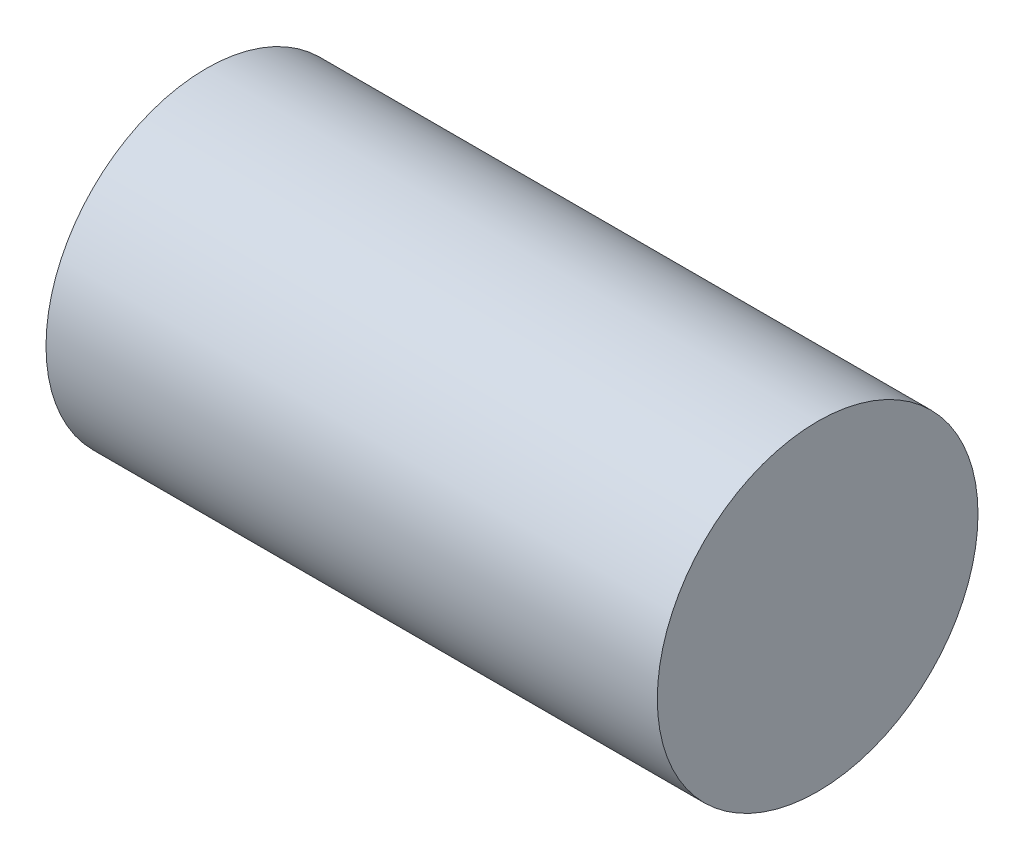
SolidWorks part; units mm, degrees
ref_plane "前视基准面" through (0, 0, 0) normal (0, 0, 1) x (1, 0, 0)
ref_plane "上视基准面" through (0, 0, 0) normal (0, 1, 0) x (1, 0, 0)
ref_plane "右视基准面" through (0, 0, 0) normal (1, 0, 0) x (0, 0, -1)
sketch "Sketch1" plane through (0, 0, 0) normal (1, 0, 0) x (0, 0, -1)
  circle A0 centre (0, 0) radius 16
extrude "Boss-Extrude1" add sketch "Sketch1" along normal blind 61
sketch "Sketch2" plane through (0, 0, 0) normal (-1, 0, 0) x (0, 0, 1)
  circle A0 centre (0, 0) radius 11
extrude "Boss-Extrude2" add sketch "Sketch2" along normal blind 2
sketch "Sketch3" plane through (0, 0, 0) normal (-1, 0, 0) x (0, 0, 1)
  circle A0 centre (0, 0) radius 13.5 construction
  circle A1 centre (0, 13.5) radius 1.5
  circle A2 centre (11.6913, 6.75) radius 1.5
  circle A3 centre (11.6913, -6.75) radius 1.5
  circle A4 centre (0, -13.5) radius 1.5
  circle A5 centre (-11.6913, -6.75) radius 1.5
  circle A6 centre (-11.6913, 6.75) radius 1.5
  dimension "D1" = 6
extrude "Cut-Extrude1" cut sketch "Sketch3" against normal blind 4
sketch "Sketch4" plane through (-2, 0, 0) normal (-1, 0, 0) x (0, 0, 1)
  circle A0 centre (0, 0) radius 2.5
  dimension "D1" = 5
extrude "Cut-Extrude2" cut sketch "Sketch4" against normal blind 2
